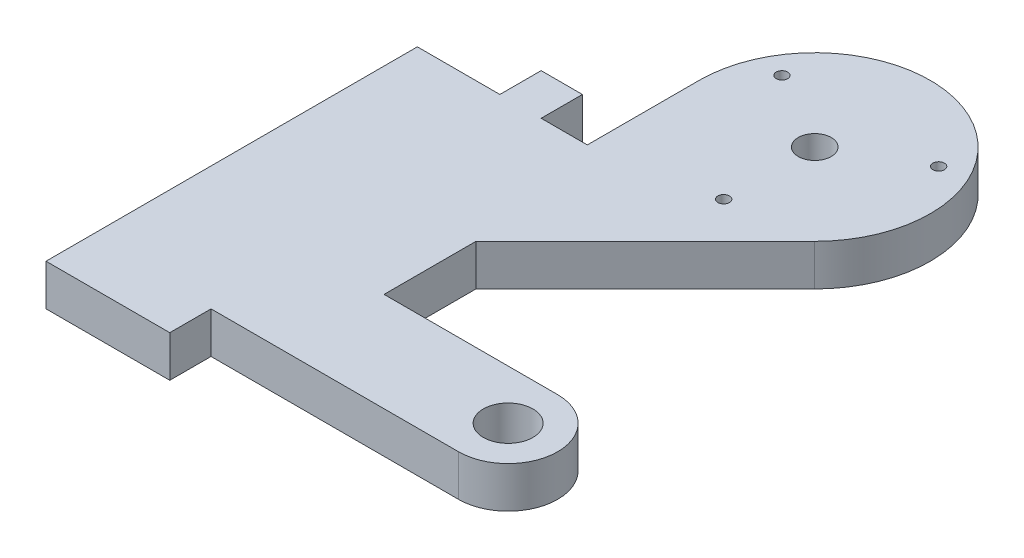
SolidWorks part; units mm, degrees
ref_plane "Front Plane" through (0, 0, 0) normal (0, 0, 1) x (1, 0, 0)
ref_plane "Top Plane" through (0, 0, 0) normal (0, 1, 0) x (1, 0, 0)
ref_plane "Right Plane" through (0, 0, 0) normal (1, 0, 0) x (0, 0, -1)
sketch "Sketch1" plane through (0, 0, 0) normal (0, 1, 0) x (1, 0, 0)
  line L1 (0, 0) -> (45, 0)
  line L2 (0, 0) -> (0, 12)
  line L3 (0, 12) -> (45, 12)
  line L5 (0, 0) -> (15, 0)
  line L6 (0, 0) -> (0, -5)
  line L7 (0, -5) -> (15, -5)
  line L8 (15, 0) -> (15, -5)
  line L9 (0, 12) -> (24, 12)
  line L10 (0, 12) -> (0, 55.0692)
  line L11 (0, 55.0692) -> (24, 55.0692)
  line L12 (24, 12) -> (24, 55.0692)
  circle A0 centre (45, 6) radius 3
  arc A1 (45, 0) -> (45, 12) centre (45, 6) ccw
  circle A6 centre (12, 53.0692) radius 0.7
  circle A7 centre (21.5263, 36.5692) radius 0.7
  circle A8 centre (2.4737, 36.5692) radius 0.7
  circle A11 centre (12, 42.0692) radius 2
  dimension "D4" = 45
  dimension "D3" = 6
  dimension "D11" = 1.4
  dimension "D1" = 5
  dimension "D2" = 15
  dimension "D5" = 6
  dimension "D13" = 3
sketch "Sketch2" plane through (0, 0, 0) normal (0, 1, 0) x (1, 0, 0)
  line L0 (20.5944, 53.5625) -> (20.5944, 40)
  line L1 (0, 0) -> (15, 0)
  line L2 (0, 0) -> (0, -5)
  line L3 (0, -5) -> (15, -5)
  line L4 (15, 0) -> (15, -5)
  line L5 (0, 0) -> (23.9647, 0)
  line L6 (0, 0) -> (0, 40)
  line L7 (0, 40) -> (23.9647, 40)
  line L8 (23.9647, 0) -> (23.9647, 40)
  line L9 (15, 40) -> (10, 40)
  line L10 (15, 40) -> (15, 45)
  line L11 (15, 45) -> (10, 45)
  line L12 (10, 40) -> (10, 45)
  line L17 (27.1777, 26.3469) -> (44.4939, 43.6631)
  line L18 (44.4939, 43.6631) -> (23.9647, 23.1339)
  line L19 (45, 12) -> (23.9647, 12)
  line L20 (45, 0) -> (23.9647, 0)
  circle A0 centre (45, 6) radius 39.6875 construction
  circle A1 centre (34.5944, 53.5625) radius 9 construction
  arc A2 (45, 0) -> (45, 12) centre (45, 6) ccw
  circle A3 centre (45, 6) radius 3
  circle A4 centre (34.5574, 42.5626) radius 0.7
  circle A8 centre (25.0866, 59.0945) radius 0.7
  circle A9 centre (44.1391, 59.0305) radius 0.7
  circle A10 centre (34.5944, 53.5625) radius 14
  circle A11 centre (34.5944, 53.5625) radius 2
  dimension "D5" = 79.375
  dimension "D6" = 18
  dimension "D7" = 11
  dimension "D8" = 3
  dimension "D9" = 45
  dimension "D1" = 40
  dimension "D2" = 5
  dimension "D3" = 5
  dimension "D4" = 0
extrude "Boss-Extrude2" add sketch "Sketch2" along normal blind 5
